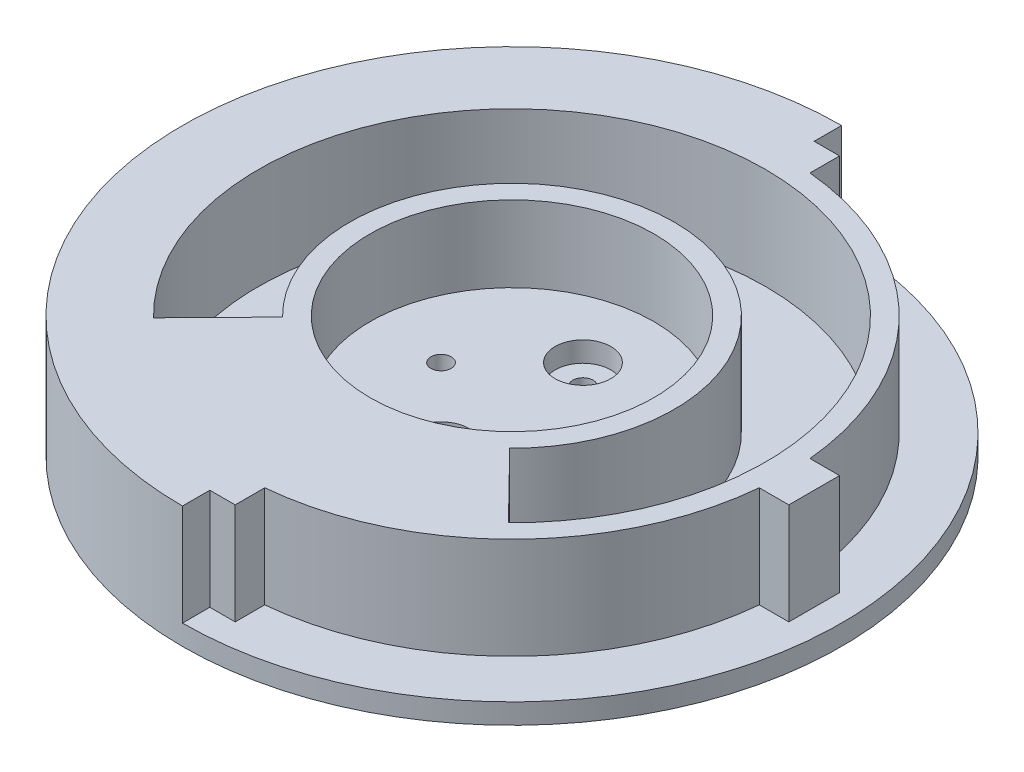
SolidWorks part; units mm, degrees
ref_plane "Front Plane" through (0, 0, 0) normal (0, 0, 1) x (1, 0, 0)
ref_plane "Top Plane" through (0, 0, 0) normal (0, 1, 0) x (1, 0, 0)
ref_plane "Right Plane" through (0, 0, 0) normal (1, 0, 0) x (0, 0, -1)
sketch "Sketch1" plane through (0, 0, 0) normal (0, 1, 0) x (1, 0, 0)
  line L0 (-17.5, -17.8536) -> (-11.2, -11.4263)
  line L1 (0, -55) -> (0, 55) construction
  line L2 (17.5, -17.8536) -> (11.2, -11.4263)
  line L4 (-17.5, -17.8536) -> (3.8221, -38.7535) construction
  circle A0 centre (0, 0) radius 27
  arc A1 (11.2, -11.4263) -> (-11.2, -11.4263) centre (0, 0) ccw
  arc A2 (17.5, -17.8536) -> (-17.5, -17.8536) centre (0, 0) ccw
  circle A3 centre (0, 0) radius 14
  arc A4 (16.5039, 11.7639) -> (14.35, -14.6399) centre (0.1913, -0.1952) cw construction
  circle A5 centre (0, 0) radius 19.9533 construction
  dimension "D1" = 54
  dimension "D2" = 2
  dimension "D3" = 9
  dimension "D4" = 2
  dimension "D5" = 35
extrude "Boss-Extrude1" add sketch "Sketch1" along normal blind 10
sketch "Sketch2" plane through (0, 0, 0) normal (0, -1, 0) x (1, 0, 0)
  circle A0 centre (0, 0) radius 32.5
  circle A1 centre (0, 0) radius 14 construction
  circle A2 centre (0, 0) radius 14 construction
  dimension "D1" = 65
extrude "Boss-Extrude2" add sketch "Sketch2" along normal blind 2
sketch "Sketch3" plane through (0, 0, 0) normal (0, 1, 0) x (1, 0, 0)
  line L0 (0, -5.5) -> (0, 5.5) construction
  line L1 (-2.5, 29.8) -> (2.5, 29.8)
  line L2 (-2.5, 29.8) -> (-2.5, 25.4032)
  line L3 (-2.5, 25.4032) -> (2.5, 25.4032)
  line L4 (2.5, 29.8) -> (2.5, 25.4032)
  line L5 (-2.5, 29.8) -> (2.5, 25.4032) construction
  line L6 (-2.5, 25.4032) -> (2.5, 29.8) construction
  line L7 (29.8, 2.5) -> (25.4032, 2.5)
  line L8 (29.8, 2.5) -> (29.8, -2.5)
  line L9 (29.8, -2.5) -> (25.4032, -2.5)
  line L10 (25.4032, 2.5) -> (25.4032, -2.5)
  line L11 (2.5, -29.8) -> (2.5, -25.4032)
  line L12 (2.5, -29.8) -> (-2.5, -29.8)
  line L13 (-2.5, -29.8) -> (-2.5, -25.4032)
  line L14 (2.5, -25.4032) -> (-2.5, -25.4032)
  line L15 (-29.8, -2.5) -> (-25.4032, -2.5)
  line L16 (-29.8, -2.5) -> (-29.8, 2.5)
  line L17 (-29.8, 2.5) -> (-25.4032, 2.5)
  line L18 (-25.4032, -2.5) -> (-25.4032, 2.5)
  circle A1 centre (0, 0) radius 27 construction
  point P0 (0, 27.6016)
  dimension "D2" = 29.8
  dimension "D1" = 5
  dimension "D3" = 4
extrude "Boss-Extrude3" add sketch "Sketch3" along normal blind 10
sketch "Sketch5" plane through (0, 0, 0) normal (0, 1, 0) x (1, 0, 0)
  line L0 (0, 29.8) -> (0, 32.5)
  line L1 (2.5, 29.8) -> (-2.5, 29.8) construction
  line L2 (0, -6.6) -> (0, 6.6) construction
  line L3 (0, -29.8) -> (0, -32.5)
  line L4 (0, 29.8) -> (-2.5, 29.8)
  line L5 (-2.5, 29.8) -> (-2.5, 26.884)
  line L6 (-26.884, 2.5) -> (-29.8, 2.5)
  line L7 (-29.8, 2.5) -> (-29.8, -2.5)
  line L8 (-29.8, -2.5) -> (-26.884, -2.5)
  line L9 (-2.5, -26.884) -> (-2.5, -29.8)
  line L10 (-2.5, -29.8) -> (0, -29.8)
  line L11 (-2.5, -29.8) -> (2.5, -29.8) construction
  circle A0 centre (0, 0) radius 32.5 construction
  arc A1 (0, 32.5) -> (0, -32.5) centre (0, 0) ccw
  arc A2 (-26.884, 2.5) -> (-2.5, 26.884) centre (0, 0) cw
  arc A3 (-26.884, -2.5) -> (-2.5, -26.884) centre (0, 0) ccw
extrude "Boss-Extrude4" add sketch "Sketch5" along normal up to surface (10 mm away) up to face at (0, 10, 0)
ref_plane "Plane1" through (0, 2.5, 0) normal (0, 1, 0) x (1, 0, 0)
sketch "Sketch6" plane through (0, 2.5, 0) normal (0, 1, 0) x (1, 0, 0)
  circle A0 centre (0, 0) radius 14
extrude "Boss-Extrude5" add sketch "Sketch6" against normal up to surface (2.5 mm away) up to face at (0, 0, 14)
sketch "Sketch4" plane through (0, -2, 0) normal (0, -1, 0) x (1, 0, 0)
  circle A0 centre (0, 0) radius 7 construction
  circle A1 centre (0, -7) radius 1
  circle A2 centre (-7, 0) radius 1
  circle A3 centre (0, 7) radius 1
  circle A4 centre (7, 0) radius 1
  point P14 (0, 0)
  dimension "D1" = 14
  dimension "D2" = 2
  dimension "D3" = 4
extrude "Cut-Extrude1" cut sketch "Sketch4" against normal through all both and the other way through all
sketch "Sketch7" plane through (0, 10, 0) normal (0, 1, 0) x (1, 0, 0)
  line L0 (11.2, -11.4263) -> (17.5, -17.8536) construction
  circle A0 centre (0, 0) radius 20.5 construction
  circle A1 centre (0, -20.5) radius 1.6
  point P5 (14.35, -14.6399)
  dimension "D1" = 3.2
extrude "Cut-Extrude2" [suppressed] cut sketch "Sketch7" against normal through all both and the other way through all
sketch "Sketch8" [suppressed] plane through (0, -2, 0) normal (0, -1, 0) x (1, 0, 0)
  line L0 (6.6, 0) -> (-6.6, 0) construction
  line L1 (-3.1177, 20.5) -> (-1.5588, 17.8)
  line L2 (-1.5588, 17.8) -> (1.5588, 17.8)
  line L3 (1.5588, 17.8) -> (3.1177, 20.5)
  line L4 (3.1177, 20.5) -> (1.5588, 23.2)
  line L5 (1.5588, 23.2) -> (-1.5588, 23.2)
  line L6 (-1.5588, 23.2) -> (-3.1177, 20.5)
  circle A0 centre (0, 20.5) radius 2.7 construction
  dimension "D1" = 5.4
extrude "Cut-Extrude3" [suppressed] cut sketch "Sketch8" against normal blind 4
sketch "Sketch9" [suppressed] plane through (0, 0, 0) normal (1, 0, 0) x (0, 0, -1)
  line L0 (32.5, 10) -> (-32.5, 10) construction
  line L1 (36, -2) -> (30.5, -2)
  line L3 (36, 10) -> (30.5, 10)
  line L4 (30.5, -2) -> (30.5, 10)
  line L5 (32.5, 10) -> (32.5, 0) construction
  arc A0 (36, -2) -> (36, 10) centre (36, 4) ccw
  circle A1 centre (36, 4) radius 1.6
  circle A2 centre (36, 4) radius 3 construction
  dimension "D4" = 3.2
  dimension "D5" = 6
  dimension "D1" = 3.5
  dimension "D2" = 2
  dimension "D3" = 12
extrude "Boss-Extrude6" [suppressed] add sketch "Sketch9" against normal blind 2
mirror "Mirror1" [suppressed] about plane through (0, 0, 0) normal (0, 0, 1)
sketch "Sketch10" plane through (0, 2.5, 0) normal (0, 1, 0) x (1, 0, 0)
  circle A0 centre (0, 7) radius 2.75
  circle A1 centre (0, -7) radius 2.75
  dimension "D1" = 5.5
  dimension "D2" = 5.5
extrude "Cut-Extrude4" cut sketch "Sketch10" against normal blind 2
sketch "Sketch11" plane through (0, -2, 0) normal (0, -1, 0) x (1, 0, 0)
  circle A0 centre (0, 0) radius 4.25
  dimension "D1" = 8.5
extrude "Cut-Extrude5" cut sketch "Sketch11" against normal blind 1
